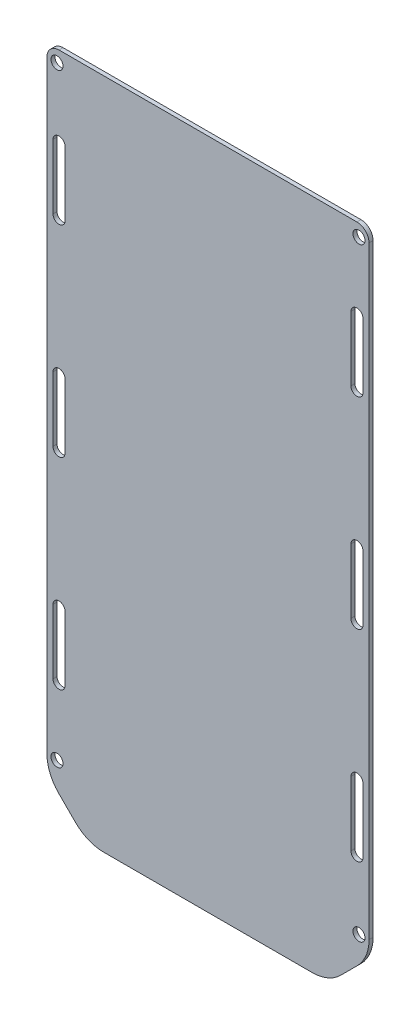
SolidWorks part; units mm, degrees
ref_plane "Front Plane" through (0, 0, 0) normal (0, 0, 1) x (1, 0, 0)
ref_plane "Top Plane" through (0, 0, 0) normal (0, 1, 0) x (1, 0, 0)
ref_plane "Right Plane" through (0, 0, 0) normal (1, 0, 0) x (0, 0, -1)
sketch "Sketch2" plane through (0, 0, 0) normal (0, 0, 1) x (1, 0, 0)
  line L0 (-10, -4) -> (49990, -4) construction
  line L1 (-47, 85) -> (27, 85)
  line L2 (-35.8579, -93) -> (15.8579, -93)
  line L3 (-42.9289, -90.0711) -> (-47.0711, -85.9289)
  line L4 (22.9289, -90.0711) -> (27.0711, -85.9289)
  line L5 (-50, 85) -> (30, -93) construction
  line L6 (-50, -93) -> (30, 85) construction
  line L7 (-10, -4) -> (-10, 49996) construction
  line L8 (-47, -12) -> (-47, 4) construction
  line L9 (-48.5, -12) -> (-48.5, 4)
  line L10 (-45.5, -12) -> (-45.5, 4)
  line L11 (27, -12) -> (27, 4) construction
  line L12 (28.5, -12) -> (28.5, 4)
  line L13 (25.5, -12) -> (25.5, 4)
  line L14 (-47, 38) -> (-47, 54) construction
  line L15 (-48.5, 38) -> (-48.5, 54)
  line L16 (-45.5, 38) -> (-45.5, 54)
  line L17 (-47, -46) -> (-47, -62) construction
  line L18 (-45.5, -46) -> (-45.5, -62)
  line L19 (-48.5, -46) -> (-48.5, -62)
  line L20 (27, 38) -> (27, 54) construction
  line L21 (28.5, 38) -> (28.5, 54)
  line L22 (25.5, 38) -> (25.5, 54)
  line L23 (27, -46) -> (27, -62) construction
  line L24 (25.5, -46) -> (25.5, -62)
  line L25 (28.5, -46) -> (28.5, -62)
  line L26 (-50, -78.8579) -> (-50, 71)
  line L27 (30, -78.8579) -> (30, 71)
  line L28 (-47, 74) -> (27, 74)
  circle A0 centre (-47.5, 71) radius 1.5
  arc A1 (-47.0711, -85.9289) -> (-50, -78.8579) centre (-40, -78.8579) cw
  arc A2 (27.0711, -85.9289) -> (30, -78.8579) centre (20, -78.8579) ccw
  arc A3 (30, 82) -> (27, 85) centre (27, 82) ccw
  arc A4 (-50, 82) -> (-47, 85) centre (-47, 82) cw
  arc A5 (-48.5, -12) -> (-45.5, -12) centre (-47, -12) ccw
  arc A6 (-45.5, 4) -> (-48.5, 4) centre (-47, 4) ccw
  arc A7 (28.5, -12) -> (25.5, -12) centre (27, -12) cw
  arc A8 (25.5, 4) -> (28.5, 4) centre (27, 4) cw
  circle A9 centre (27.5, 71) radius 1.5
  circle A10 centre (-47.5, -79) radius 1.5
  circle A11 centre (27.5, -79) radius 1.5
  arc A12 (-48.5, 38) -> (-45.5, 38) centre (-47, 38) ccw
  arc A13 (-45.5, 54) -> (-48.5, 54) centre (-47, 54) ccw
  arc A14 (-45.5, -46) -> (-48.5, -46) centre (-47, -46) ccw
  arc A15 (-48.5, -62) -> (-45.5, -62) centre (-47, -62) ccw
  arc A16 (28.5, 38) -> (25.5, 38) centre (27, 38) cw
  arc A17 (25.5, 54) -> (28.5, 54) centre (27, 54) cw
  arc A18 (25.5, -46) -> (28.5, -46) centre (27, -46) cw
  arc A19 (28.5, -62) -> (25.5, -62) centre (27, -62) cw
  arc A20 (30, 71) -> (27, 74) centre (27, 71) ccw
  arc A21 (-50, 71) -> (-47, 74) centre (-47, 71) cw
  arc A22 (22.9289, -90.0711) -> (15.8579, -93) centre (15.8579, -83) cw
  arc A23 (-35.8579, -93) -> (-42.9289, -90.0711) centre (-35.8579, -83) cw
  point P0 (-10, -4)
  point P23 (-50, -83)
  point P26 (-47, -4)
  point P33 (27, -4)
  point P46 (-47, 46)
  point P53 (-47, -54)
  point P60 (27, 46)
  point P67 (27, -54)
  point P77 (30, 74)
  point P80 (-50, 74)
  point P82 (30, -83)
  point P85 (20, -93)
  point P88 (-40, -93)
  dimension "D3" = 37.5
  dimension "D5" = 10
  dimension "D7" = 50
  dimension "D9" = 3
  dimension "D12" = 3
  dimension "D1" = 80
  dimension "D2" = 178
  dimension "D4" = 75
  dimension "D8" = 50
extrude "Boss-Extrude1" add sketch "Sketch2" along normal blind 1
